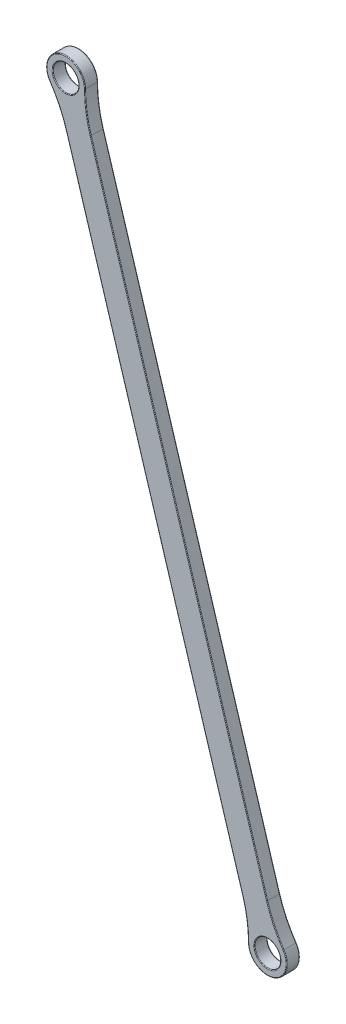
SolidWorks part; units mm, degrees
ref_plane "前视基准面" through (0, 0, 0) normal (0, 0, 1) x (1, 0, 0)
ref_plane "上视基准面" through (0, 0, 0) normal (0, 1, 0) x (1, 0, 0)
ref_plane "右视基准面" through (0, 0, 0) normal (1, 0, 0) x (0, 0, -1)
sketch "草图1" plane through (0, 0, 0) normal (0, 0, 1) x (1, 0, 0)
  line L0 (33.7467, 59.4755) -> (-13.2252, 212.4253) construction
  line L1 (33.7467, 59.4755) -> (-13.2252, 212.4253) construction
  line L2 (33.7467, 59.4755) -> (-13.2252, 212.4253) construction
  line L3 (30.8789, 58.5948) -> (-16.093, 211.5446)
  line L4 (36.6145, 60.3562) -> (-10.3574, 213.306)
  circle A0 centre (-13.2252, 212.4253) radius 4.5
  circle A1 centre (33.7467, 59.4755) radius 4.5
  arc A2 (30.8789, 58.5948) -> (36.6145, 60.3562) centre (33.7467, 59.4755) ccw
  arc A3 (-10.3574, 213.306) -> (-16.093, 211.5446) centre (-13.2252, 212.4253) ccw
  arc A4 (-16.093, 211.5446) -> (-10.3574, 213.306) centre (-13.2252, 212.4253) ccw
  arc A5 (36.6145, 60.3562) -> (30.8789, 58.5948) centre (33.7467, 59.4755) ccw
  point P5 (10.2607, 135.9504)
  dimension "D1" = 9
  dimension "D2" = 6
extrude "凸台-拉伸1" add sketch "草图1" against normal blind 3 contours A1 L4 A0 L3 | A2 L3 A1 L4 | A3 L4 A0 L3 | A4 L3 A0 L4 | A5 L4 A1 L3
fillet "圆角1" radius 30 4 edges at (-15.1084, 208.3383, -1.5) (-9.3727, 210.0997, -1.5) (35.6299, 63.5625, -1.5) (29.8942, 61.8011, -1.5)
fillet "圆角2" radius 0.15 20 edges at (36.7467, 59.4755, -3) (35.2725, 65.8431, -3) (13.1286, 136.8311, -3) (-8.3885, 208.0117, -3) (-14.5463, 216.727, -3) (-14.751, 206.0577, -3) (7.3929, 135.0697, -3) (28.91, 63.8891, -3) (35.0678, 55.1738, -3) (-10.2252, 212.4253, -3) (36.7467, 59.4755, 0) (-14.751, 206.0577, 0) (-14.5463, 216.727, 0) (-8.3885, 208.0117, 0) (13.1286, 136.8311, 0) (35.2725, 65.8431, 0) (35.0678, 55.1738, 0) (28.91, 63.8891, 0) (7.3929, 135.0697, 0) (-10.2252, 212.4253, 0)
